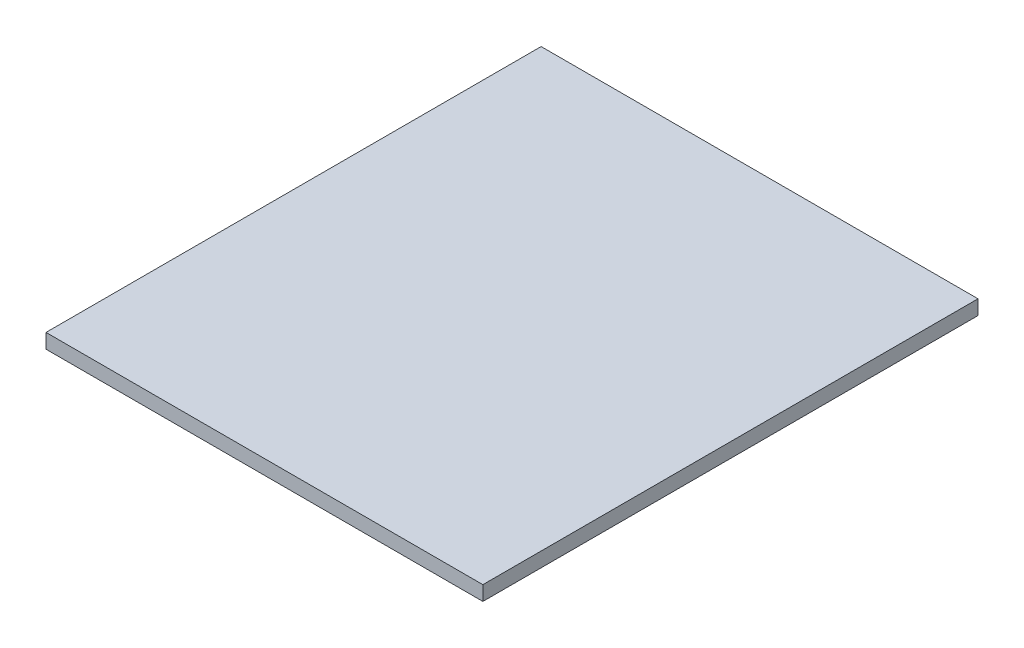
SolidWorks part; units mm, degrees
ref_plane "Front Plane" through (0, 0, 0) normal (0, 0, 1) x (1, 0, 0)
ref_plane "Top Plane" through (0, 0, 0) normal (0, 1, 0) x (1, 0, 0)
ref_plane "Right Plane" through (0, 0, 0) normal (1, 0, 0) x (0, 0, -1)
sketch "Sketch1" plane through (0, 0, 0) normal (0, 1, 0) x (1, 0, 0)
  line L1 (-77.3921, 130.0375) -> (72.6079, 130.0375)
  line L2 (-77.3921, 130.0375) -> (-77.3921, -39.9625)
  line L3 (-77.3921, -39.9625) -> (72.6079, -39.9625)
  line L4 (72.6079, 130.0375) -> (72.6079, -39.9625)
  dimension "D1" = 150
  dimension "D2" = 170
extrude "Boss-Extrude1" add sketch "Sketch1" along normal blind 5
